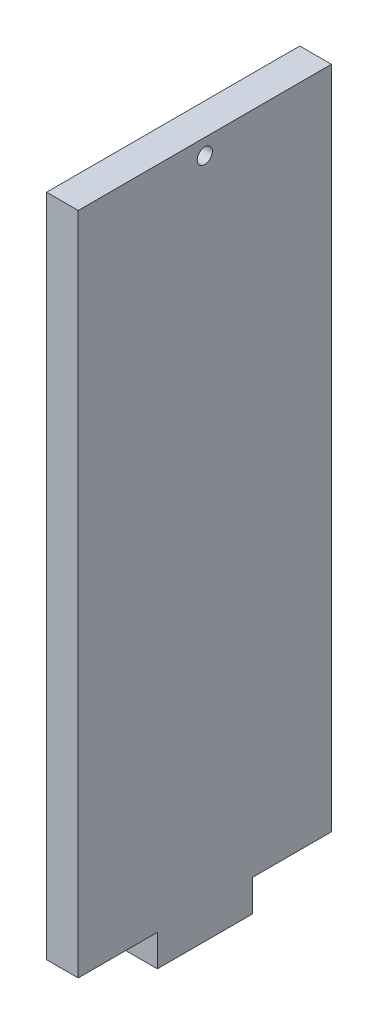
SolidWorks part; units mm, degrees
ref_plane "Front Plane" through (0, 0, 0) normal (0, 0, 1) x (1, 0, 0)
ref_plane "Top Plane" through (0, 0, 0) normal (0, 1, 0) x (1, 0, 0)
ref_plane "Right Plane" through (0, 0, 0) normal (1, 0, 0) x (0, 0, -1)
sketch "Sketch2" plane through (0, 0, 0) normal (1, 0, 0) x (0, 0, -1)
  line L1 (0, 0) -> (50.8, 0)
  line L2 (0, 0) -> (0, 127)
  line L3 (0, 127) -> (50.8, 127)
  line L4 (50.8, 0) -> (50.8, 127)
  dimension "D1" = 127
  dimension "D2" = 50.8
extrude "Boss-Extrude1" add sketch "Sketch2" along normal blind 6.35
sketch "Sketch3" plane through (6.35, 0, 0) normal (1, 0, 0) x (0, 0, -1)
  line L0 (3.4925, 0) -> (-3.4925, 0) construction
  line L1 (15.875, 0) -> (34.925, 0)
  line L2 (15.875, 0) -> (15.875, -6.35)
  line L3 (15.875, -6.35) -> (34.925, -6.35)
  line L4 (34.925, 0) -> (34.925, -6.35)
  line L6 (0, 0) -> (50.8, 0) construction
  line L7 (0, 0) -> (50.8, 0) construction
  point P6 (25.4, 0)
  dimension "D1" = 19.05
  dimension "D3" = 6.35
extrude "Boss-Extrude2" add sketch "Sketch3" against normal blind 6.35
sketch "Sketch5" plane through (0, 0, 0) normal (-1, 0, 0) x (0, 0, 1)
  line L0 (0, -3.4925) -> (0, 3.4925) construction
  line L1 (-50.8, 127) -> (0, 127)
  line L2 (-50.8, 127) -> (-50.8, 133.35)
  line L3 (-50.8, 133.35) -> (0, 133.35)
  line L4 (0, 127) -> (0, 133.35)
  dimension "D1" = 6.35
extrude "Boss-Extrude3" add sketch "Sketch5" against normal blind 6.35
sketch "Sketch6" plane through (6.35, 0, 0) normal (1, 0, 0) x (0, 0, -1)
  line L0 (0, 130.175) -> (50.8, 130.175) construction
  line L1 (0, 3.4925) -> (0, -3.4925) construction
  line L2 (50.8, 0) -> (50.8, 133.35) construction
  line L3 (0, 133.35) -> (50.8, 133.35) construction
  circle A0 centre (25.4, 130.175) radius 1.524
  dimension "D2" = 3.048
  dimension "D1" = 3.175
extrude "Cut-Extrude1" cut sketch "Sketch6" against normal through all
